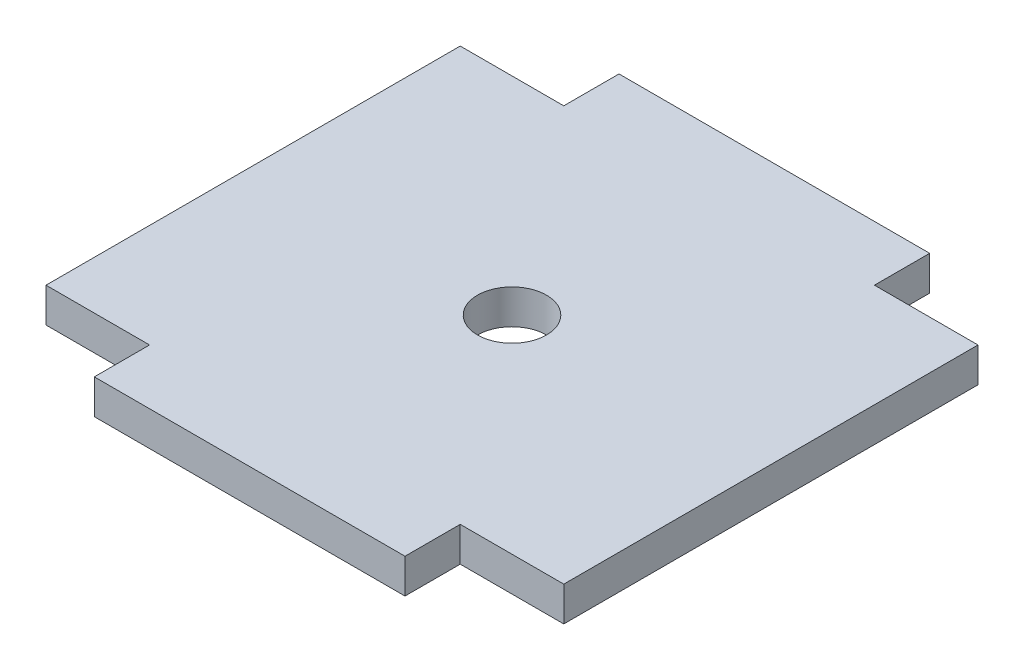
SolidWorks part; units mm, degrees
ref_plane "Piano frontale" through (0, 0, 0) normal (0, 0, 1) x (1, 0, 0)
ref_plane "Piano superiore" through (0, 0, 0) normal (0, 1, 0) x (1, 0, 0)
ref_plane "Piano destro" through (0, 0, 0) normal (1, 0, 0) x (0, 0, -1)
sketch "Schizzo1" plane through (0, 0, 0) normal (0, 1, 0) x (1, 0, 0)
  line L1 (-37.5, -30) -> (37.5, -30)
  line L2 (-37.5, -30) -> (-37.5, 30)
  line L3 (-37.5, 30) -> (37.5, 30)
  line L4 (37.5, -30) -> (37.5, 30)
  line L5 (-37.5, -30) -> (37.5, 30) construction
  line L6 (-37.5, 30) -> (37.5, -30) construction
  point P0 (0, 0)
  dimension "D1" = 60
  dimension "D2" = 75
extrude "Estrusione-Estrusione1" add sketch "Schizzo1" along normal blind 5
sketch "Schizzo2" plane through (0, 5, 0) normal (0, 1, 0) x (-1, 0, 0)
  circle A0 centre (0, 0) radius 5
  dimension "D1" = 10
extrude "Taglio-Estrusione1" cut sketch "Schizzo2" against normal through all
sketch "Schizzo3" plane through (0, 0, 30) normal (0, 0, 1) x (1, 0, 0)
  line L0 (-37.5, 5) -> (37.5, 5) construction
  line L1 (-22.5, 0) -> (22.5, 0)
  line L2 (-22.5, 0) -> (-22.5, 5)
  line L3 (-22.5, 5) -> (22.5, 5)
  line L4 (22.5, 0) -> (22.5, 5)
  line L5 (-22.5, 0) -> (22.5, 5) construction
  line L6 (-22.5, 5) -> (22.5, 0) construction
  line L7 (-37.5, 5) -> (-37.5, 0) construction
  point P0 (0, 2.5)
  dimension "D1" = 45
  dimension "D2" = 5
  dimension "D3" = 15
extrude "Estrusione-Estrusione2" add sketch "Schizzo3" along normal blind 8
mirror "Specchia1" about plane through (0, 0, 0) normal (0, 0, 1) of "Estrusione-Estrusione2"
